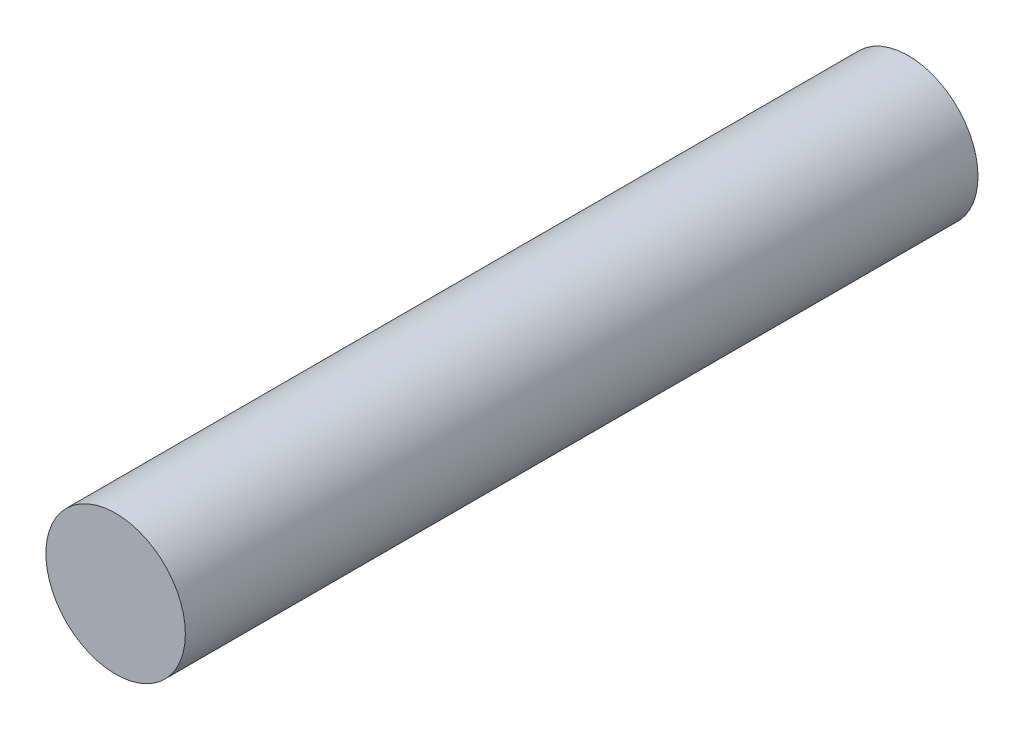
SolidWorks part; units mm, degrees
ref_plane "Plan de face" through (0, 0, 0) normal (0, 0, 1) x (1, 0, 0)
ref_plane "Plan de dessus" through (0, 0, 0) normal (0, 1, 0) x (1, 0, 0)
ref_plane "Plan de droite" through (0, 0, 0) normal (1, 0, 0) x (0, 0, -1)
sketch "Esquisse1" plane through (0, 0, 0) normal (0, 0, 1) x (1, 0, 0)
  circle A0 centre (0, 0) radius 22
extrude "Boss.-Extru.1" add sketch "Esquisse1" along normal blind 250
